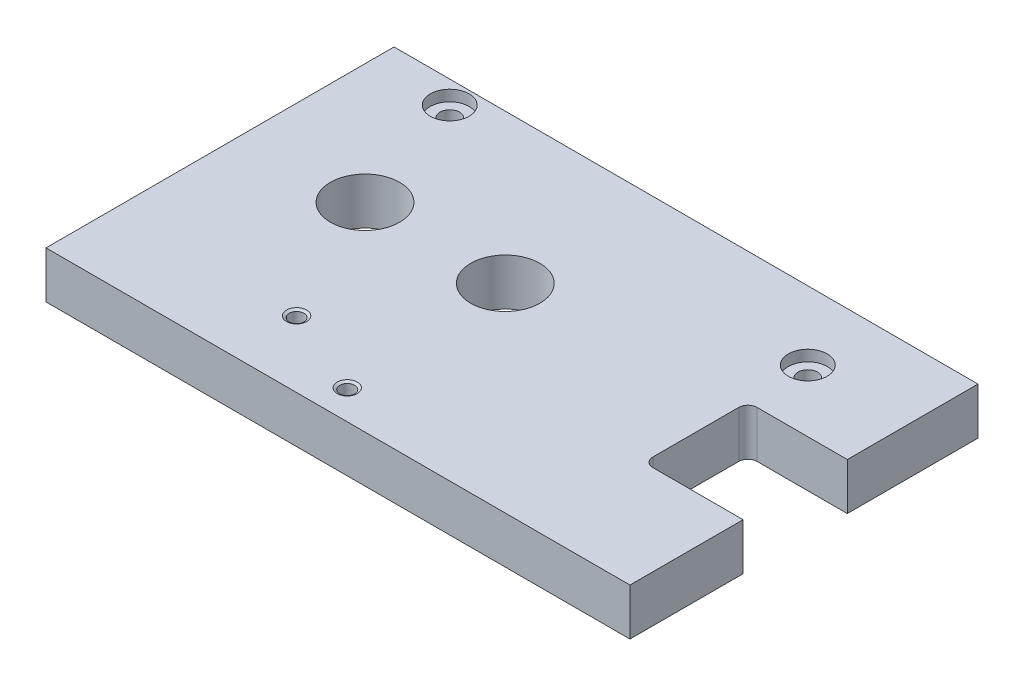
SolidWorks part; units mm, degrees
material "1060 Alloy"
ref_plane "Front Plane" through (0, 0, 0) normal (0, 0, 1) x (1, 0, 0)
ref_plane "Top Plane" through (0, 0, 0) normal (0, 1, 0) x (1, 0, 0)
ref_plane "Right Plane" through (0, 0, 0) normal (1, 0, 0) x (0, 0, -1)
sketch "Sketch1" plane through (0, 0, 0) normal (0, 1, 0) x (1, 0, 0)
  line L1 (0, 0) -> (160, 0)
  line L2 (0, 0) -> (0, -95.37)
  line L3 (0, -95.37) -> (160, -95.37)
  line L4 (160, 0) -> (160, -95.37)
  dimension "D1" = 95.37
  dimension "D2" = 160
extrude "Boss-Extrude3" add sketch "Sketch1" along normal blind 12.83
hole_wizard "Hole1" positions "Sketch3" profile "Sketch2" legacy end condition through all
sketch "Sketch3" plane through (0, 12.83, 0) normal (0, 1, 0) x (-1, 0, 0)
  line L0 (0, 0) -> (0, 95.37) construction
  line L1 (0, 95.37) -> (-160, 95.37) construction
  point P0 (-32.885, 40.845)
  point P1 (-71.315, 40.845)
  dimension "D1" = 32.885
  dimension "D2" = 38.43
  dimension "D3" = 54.525
  dimension "D4" = 54.525
sketch "Sketch2" plane through (32.885, 12.83, 40.845) normal (1, 0, 0) x (0, 0, 1)
  line L0 (0, 0) -> (0, 12.83)
  line L1 (0, 12.83) -> (9.485, 12.83)
  line L2 (9.485, 12.83) -> (9.485, 0)
  line L3 (9.485, 0) -> (0, 0)
  line L4 (0, 110) -> (0, -10) construction
  dimension "Diameter" = 18.97
  dimension "Depth" = 12.83
sketch "Sketch4" plane through (0, 12.83, 0) normal (0, 1, 0) x (-1, 0, 0)
  line L0 (-160, 95.37) -> (-160, 0) construction
  line L1 (-160, 64.37) -> (-132.76, 64.37)
  line L2 (-160, 64.37) -> (-160, 35.81)
  line L3 (-160, 35.81) -> (-132.76, 35.81)
  line L4 (-132.76, 64.37) -> (-132.76, 35.81)
  line L5 (0, 95.37) -> (-160, 95.37) construction
  dimension "D1" = 31
  dimension "D2" = 59.56
  dimension "D3" = 27.24
extrude "Cut-Extrude1" cut sketch "Sketch4" against normal through all
fillet "Fillet1" radius 2.5 2 edges at (132.76, 6.415, 64.37) (132.76, 6.415, 35.81)
hole_wizard "Hole2" positions "Sketch6" profile "Sketch5" legacy end condition through all
sketch "Sketch6" plane through (0, 12.83, 0) normal (0, 1, 0) x (-1, 0, 0)
  line L0 (-160, 0) -> (0, 0) construction
  line L1 (0, 0) -> (0, 95.37) construction
  line L2 (-160, 35.81) -> (-160, 0) construction
  point P0 (-21.425, 6.17)
  point P1 (-132.175, 18.815)
  dimension "D1" = 6.17
  dimension "D2" = 21.425
  dimension "D3" = 18.815
  dimension "D4" = 27.825
sketch "Sketch5" plane through (21.425, 12.83, 6.17) normal (1, 0, 0) x (0, 0, 1)
  line L0 (0, 0) -> (0, 12.83)
  line L1 (0, 12.83) -> (2.675, 12.83)
  line L2 (2.675, 12.83) -> (2.675, 3)
  line L3 (2.675, 3) -> (5.325, 3)
  line L4 (5.325, 3) -> (5.325, 0)
  line L5 (5.325, 0) -> (0, 0)
  line L6 (0, 110) -> (0, -10) construction
  dimension "Diameter" = 5.35
  dimension "Depth" = 12.83
  dimension "C-Bore Diameter" = 10.65
  dimension "C-Bore Depth" = 3
hole_wizard "Hole3" positions "Sketch8" profile "Sketch9" legacy end condition through all
sketch "Sketch8" plane through (0, 12.83, 0) normal (0, 1, 0) x (-1, 0, 0)
  line L0 (0, 95.37) -> (-160, 95.37) construction
  line L1 (0, 0) -> (0, 95.37) construction
  line L2 (-160, 95.37) -> (-160, 64.37) construction
  point P0 (-50.46, 77.16)
  point P1 (-74.48, 87.31)
  dimension "D1" = 18.21
  dimension "D2" = 50.46
  dimension "D3" = 8.06
  dimension "D4" = 85.52
sketch "Sketch9" plane through (50.46, 12.83, 77.16) normal (1, 0, 0) x (0, 0, 1)
  line L0 (0, 0) -> (0, 12.83)
  line L1 (0, 12.83) -> (2.04, 12.83)
  line L2 (2.04, 12.83) -> (2.04, 0.4099)
  line L3 (2.04, 0.4099) -> (2.75, 0)
  line L4 (2.75, 0) -> (0, 0)
  line L5 (0, -6.4453) -> (0, 115.525) construction
  line L6 (-2.04, 0.4099) -> (-2.75, 0) construction
  dimension "Diameter" = 4.08
  dimension "Depth" = 12.83
  dimension "C-Sink Angle" = 120
  dimension "C-Sink Diameter" = 5.5
sketch "Sketch10" plane through (0, 0, 0) normal (0, -1, 0) x (1, 0, 0)
  circle A0 centre (132.175, 18.815) radius 9.525
extrude "Cut-Extrude2" cut sketch "Sketch10" against normal blind 3.3019
sketch "Sketch11" plane through (0, 0, 0) normal (0, -1, 0) x (1, 0, 0)
  circle A0 centre (21.425, 6.17) radius 5.08
extrude "Cut-Extrude3" cut sketch "Sketch11" against normal blind 3.175
equation "\"D4@Sketch3\"=\"D3@Sketch3\""
